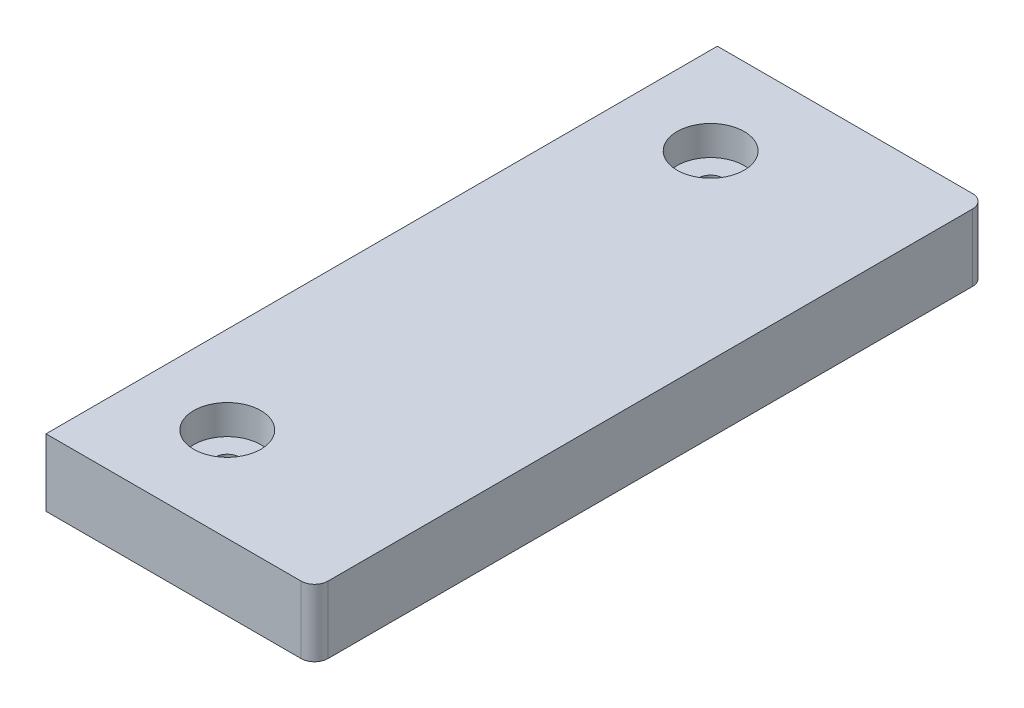
SolidWorks part; units mm, degrees
ref_plane "前视基准面" through (0, 0, 0) normal (0, 0, 1) x (1, 0, 0)
ref_plane "上视基准面" through (0, 0, 0) normal (0, 1, 0) x (1, 0, 0)
ref_plane "右视基准面" through (0, 0, 0) normal (1, 0, 0) x (0, 0, -1)
other "Configuration Table"
sketch "草图1" plane through (0, 0, 0) normal (0, 1, 0) x (1, 0, 0)
  line L1 (-50, 125) -> (45, 125)
  line L2 (-50, 125) -> (-50, -125)
  line L3 (-50, -125) -> (45, -125)
  line L4 (50, 120) -> (50, -120)
  line L6 (50, 0) -> (50, 90)
  arc A2 (45, 125) -> (50, 120) centre (45, 120) cw
  arc A3 (45, -125) -> (50, -120) centre (45, -120) ccw
  dimension "D1" = 5
  dimension "D2" = 5
extrude "凸台-拉伸1" add sketch "草图1" along normal blind 25 contours L3 A3 L4 A2 L1 L2
sketch "草图2" plane through (0, 25, 0) normal (0, 1, 0) x (1, 0, 0)
  line L0 (0, 0) -> (50, 0)
  line L1 (50, 120) -> (50, -120) construction
  line L2 (50, 0) -> (50, 90)
  circle A0 centre (-17.5, 90) radius 12.5
  circle A1 centre (-17.5, -90) radius 12.5
extrude "切除-拉伸1" cut sketch "草图2" against normal blind 11 contours A0 | A1
sketch "草图3" plane through (0, 14, 0) normal (0, 1, 0) x (1, 0, 0)
  circle A0 centre (-17.5, 90) radius 4.5
  circle A1 centre (-17.5, -90) radius 4.5
extrude "切除-拉伸2" cut sketch "草图3" against normal blind 15
sketch "草图5" plane through (0, 0, 0) normal (0, -1, 0) x (1, 0, 0)
  circle A0 centre (-17.5, 90) radius 8
  circle A1 centre (-17.5, -90) radius 8
extrude "切除-拉伸3" cut sketch "草图5" against normal blind 9
sketch "草图6" plane through (-50, 0, 0) normal (-1, 0, 0) x (0, 0, 1)
  circle A0 centre (112, 12.5) radius 4
  circle A1 centre (-112, 12.5) radius 4
extrude "切除-拉伸4" cut sketch "草图6" against normal blind 50
cosmetic thread "装饰螺纹线1" parameters "D2"=10
cosmetic thread "装饰螺纹线2" parameters "D2"=10
